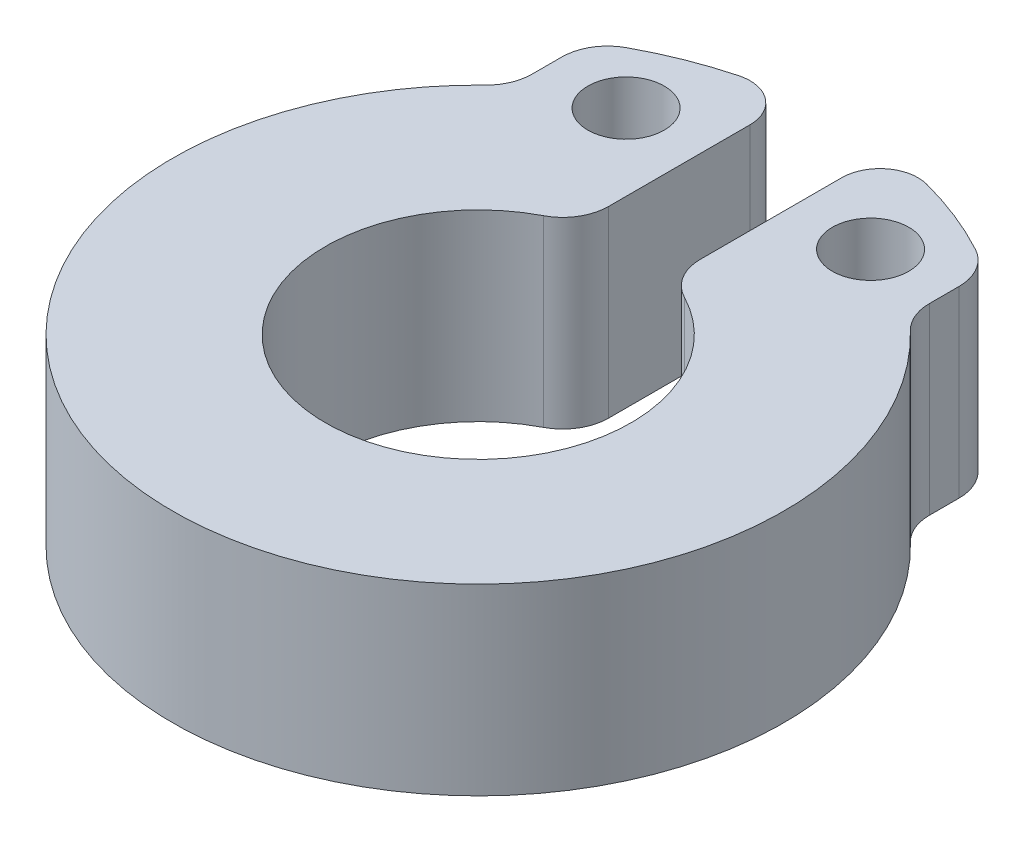
SolidWorks part; units mm, degrees
ref_plane "Front Plane" through (0, 0, 0) normal (0, 0, 1) x (1, 0, 0)
ref_plane "Top Plane" through (0, 0, 0) normal (0, 1, 0) x (1, 0, 0)
ref_plane "Right Plane" through (0, 0, 0) normal (1, 0, 0) x (0, 0, -1)
sketch "Sketch1" plane through (0, 0, 0) normal (0, 1, 0) x (1, 0, 0)
  line L0 (-0.3, 0.9539) -> (-0.3, 2.3812)
  line L1 (0.3, 0.9539) -> (0.3, 2.3812)
  line L2 (-1.3, 1.5199) -> (-1.3, 2.0174)
  line L3 (1.3, 1.5199) -> (1.3, 2.0174)
  line L4 (-1.3, 2.0174) -> (-0.3, 2.0174) construction
  line L5 (1.3, 2.0174) -> (0.3, 2.0174) construction
  arc A0 (-0.3, 0.9539) -> (0.3, 0.9539) centre (0, 0) ccw
  arc A1 (-1.3, 1.5199) -> (1.3, 1.5199) centre (0, 0) ccw
  arc A2 (1.3, 2.0174) -> (0.3, 2.3812) centre (0, 0) ccw
  circle A3 centre (0, 0) radius 2.4 construction
  arc A4 (-0.3, 2.3812) -> (-1.3, 2.0174) centre (0, 0) ccw
  circle A5 centre (0, 0) radius 2 construction
  circle A6 centre (0, 0) radius 1 construction
  circle A7 centre (-0.8, 1.7674) radius 0.25
  circle A8 centre (0.8, 1.7674) radius 0.25
  point P1 (-0.8, 2.0174)
  point P24 (0.8, 2.0174)
  dimension "D1" = 2
  dimension "D6" = 0.5
  dimension "D3" = 0.6
  dimension "D4" = 0.4
  dimension "D5" = 1
  dimension "D7" = 0.25
  dimension "D2" = 1
extrude "Boss-Extrude1" add sketch "Sketch1" along normal blind 1.2
fillet "Fillet1" radius 0.3 6 edges at (-1.3, 0.6, -2.0174) (1.3, 0.6, -2.0174) (1.3, 0.6, -1.5199) (-1.3, 0.6, -1.5199) (0.3, 0.6, -0.9539) (-0.3, 0.6, -0.9539)
fillet "Fillet2" radius 0.25 2 edges at (0.3, 0.6, -2.3812) (-0.3, 0.6, -2.3812)
